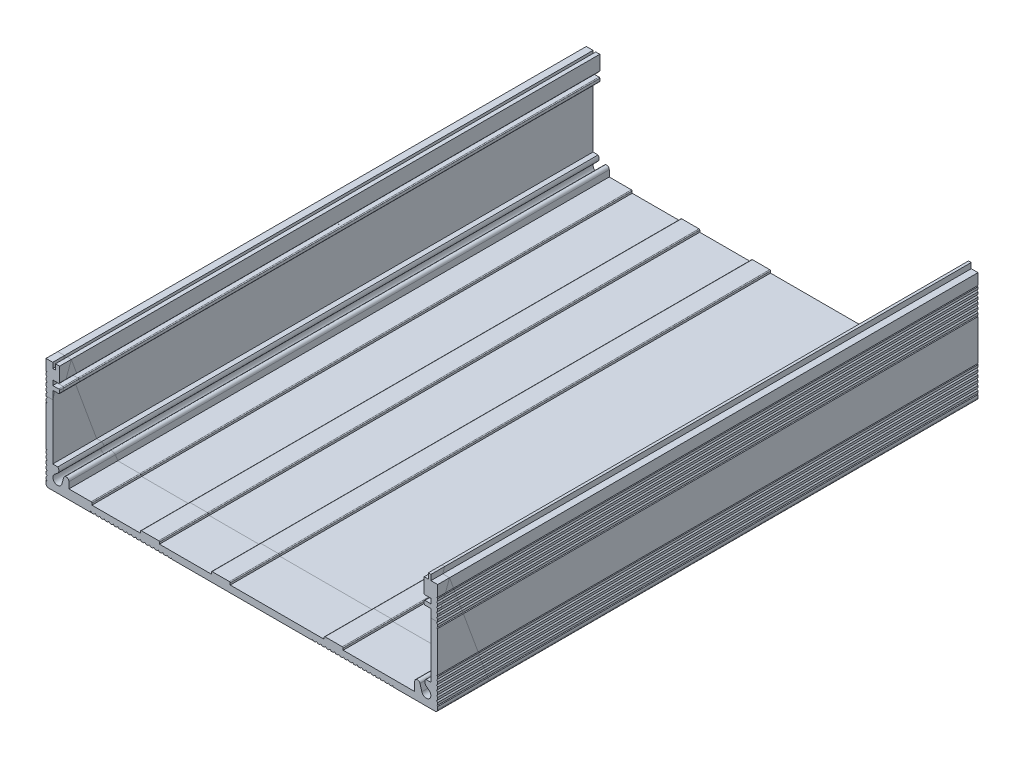
SolidWorks part; units mm, degrees
ref_plane "Front Plane" through (0, 0, 0) normal (0, 0, 1) x (1, 0, 0)
ref_plane "Top Plane" through (0, 0, 0) normal (0, 1, 0) x (1, 0, 0)
ref_plane "Right Plane" through (0, 0, 0) normal (1, 0, 0) x (0, 0, -1)
sketch "Sketch1" plane through (0, 0, 0) normal (0, 0, 1) x (1, 0, 0)
  line L2 (-72.5, -41.1) -> (-72.5, 0)
  line L11 (-70, -32.6) -> (-68.132, -32.6)
  line L12 (-69.2793, -35.507) -> (-68.3418, -34.7938)
  line L14 (-65.9634, -34.9834) -> (-66.6122, -37.3156)
  line L15 (-72.5, -41.1) -> (72.5, -41.1)
  line L17 (-70, -8.95) -> (-67.5, -8.95)
  line L18 (-67.5, -8.95) -> (-67.5, -7.45)
  line L19 (-67.5, -7.45) -> (-70, -7.45)
  line L20 (-70, -5.65) -> (-67.5, -5.65)
  line L21 (-67.5, -5.65) -> (-67.5, 0)
  line L23 (-70, -5.65) -> (-70, -7.45)
  line L24 (-70, -8.95) -> (-70, -32.6)
  line L25 (0, -46.4474) -> (0, 0) construction
  line L26 (70, -8.95) -> (70, -32.6)
  line L27 (70, -5.65) -> (70, -7.45)
  line L29 (67.5, -5.65) -> (67.5, 0)
  line L30 (70, -5.65) -> (67.5, -5.65)
  line L31 (67.5, -7.45) -> (70, -7.45)
  line L32 (67.5, -8.95) -> (67.5, -7.45)
  line L33 (70, -8.95) -> (67.5, -8.95)
  line L34 (65.9634, -34.9834) -> (66.6122, -37.3156)
  line L35 (64, -35.2514) -> (64, -38.56)
  line L36 (69.2793, -35.507) -> (68.3418, -34.7938)
  line L37 (70, -32.6) -> (68.132, -32.6)
  line L39 (72.5, -41.1) -> (72.5, 0)
  line L40 (67.5, 0) -> (69, 0)
  line L41 (69, 0) -> (69, 2)
  line L42 (69, 2) -> (70, 2)
  line L43 (70, 2) -> (70, 0)
  line L44 (70, 0) -> (72.5, 0)
  line L45 (-72.5, 0) -> (-70, 0)
  line L46 (-70, 0) -> (-70, -2)
  line L47 (-70, -2) -> (-69, -2)
  line L48 (-69, -2) -> (-69, 0)
  line L49 (-69, 0) -> (-67.5, 0)
  line L50 (-64, -37.6) -> (-55.5, -37.6)
  line L51 (-55.5, -37.6) -> (-55.5, -38.56)
  line L52 (-55.5, -38.56) -> (-37.5, -38.56)
  line L53 (-37.5, -38.56) -> (-37.5, -37.6)
  line L54 (-37.5, -37.6) -> (-30.5, -37.6)
  line L55 (-30.5, -37.6) -> (-30.5, -38.56)
  line L56 (-4.3, -38.56) -> (30.5, -38.56)
  line L57 (-4.3, -38.56) -> (-4.3, -37.6)
  line L58 (-4.3, -37.6) -> (-11.3, -37.6)
  line L59 (-11.3, -37.6) -> (-11.3, -38.56)
  line L60 (-11.3, -38.56) -> (-30.5, -38.56)
  line L61 (30.5, -38.56) -> (30.5, -37.6)
  line L62 (30.5, -37.6) -> (37.5, -37.6)
  line L63 (37.5, -37.6) -> (37.5, -38.56)
  line L64 (37.5, -38.56) -> (64, -38.56)
  line L65 (-64, -35.2514) -> (-64, -37.6)
  arc A1 (-69.2793, -35.507) -> (-66.6122, -37.3156) centre (-68.25, -36.86) ccw
  arc A3 (-68.132, -32.6) -> (-68.3418, -34.7938) centre (-69.25, -33.6) cw
  arc A4 (-65.9634, -34.9834) -> (-64, -35.2514) centre (-65, -35.2514) cw
  arc A5 (65.9634, -34.9834) -> (64, -35.2514) centre (65, -35.2514) ccw
  arc A6 (68.132, -32.6) -> (68.3418, -34.7938) centre (69.25, -33.6) ccw
  arc A7 (69.2793, -35.507) -> (66.6122, -37.3156) centre (68.25, -36.86) cw
  point P45 (0, -41.1)
  point P47 (0, -37.1)
  dimension "D5" = 8.5
  dimension "D8" = 8.5
  dimension "D9" = 1.5
  dimension "D10" = 4.24
  dimension "D4" = 35.45
  dimension "D13" = 7.5
  dimension "D6" = 1.7
  dimension "D7" = 7.5
  dimension "D32" = 136.5
  dimension "D2" = 41.1
  dimension "D3" = 72.5
  dimension "D11" = 4.25
  dimension "D12" = 3.25
  dimension "D14" = 2.5
  dimension "D15" = 33.65
  dimension "D16" = 32.15
  dimension "D17" = 5.65
  dimension "D18" = 5
  dimension "D19" = 1
  dimension "D20" = 1
  dimension "D21" = 2
  dimension "D22" = 2
  dimension "D23" = 55.5
  dimension "D24" = 30.5
  dimension "D25" = 7
  dimension "D26" = 4.3
  dimension "D27" = 7
  dimension "D28" = 7
  dimension "D29" = 30.5
  dimension "D30" = 2.54
  dimension "D31" = 3.5
extrude "Boss-Extrude1" add sketch "Sketch1" against normal blind 200
sketch "Sketch3" plane through (0, 0, 0) normal (0, 0, 1) x (1, 0, 0)
  line L0 (-72.0833, -29.1) -> (-72.9167, -29.9333)
  line L1 (-72.5, -41.1) -> (72.5, -41.1) construction
  line L2 (-72.5, 0) -> (-72.5, -41.1) construction
  line L3 (-72.0833, -29.1) -> (-75.0833, -29.1)
  line L4 (-72.0833, -30.7667) -> (-72.9167, -31.6)
  line L5 (-72.9167, -29.9333) -> (-72.0833, -30.7667)
  line L6 (-72.9167, -31.6) -> (-72.0833, -32.4333)
  line L7 (-72.0833, -32.4333) -> (-72.9167, -33.2667)
  line L8 (-72.9167, -33.2667) -> (-72.0833, -34.1)
  line L9 (-72.0833, -34.1) -> (-72.9167, -34.9333)
  line L10 (-72.9167, -34.9333) -> (-72.0833, -35.7667)
  line L11 (-72.0833, -35.7667) -> (-72.9167, -36.6)
  line L12 (-72.9167, -36.6) -> (-72.0833, -37.4333)
  line L13 (-72.0833, -37.4333) -> (-72.9167, -38.2667)
  line L14 (-72.9167, -38.2667) -> (-72.0833, -39.1)
  line L15 (-75.0833, -29.1) -> (-75.0833, -39.1)
  line L16 (-75.0833, -39.1) -> (-72.0833, -39.1)
  line L17 (0, -29.205) -> (0, 29.205) construction
  line L18 (75.0833, -29.1) -> (75.0833, -39.1)
  line L19 (72.0833, -29.1) -> (75.0833, -29.1)
  line L20 (72.0833, -29.1) -> (72.9167, -29.9333)
  line L21 (72.9167, -29.9333) -> (72.0833, -30.7667)
  line L22 (72.0833, -30.7667) -> (72.9167, -31.6)
  line L23 (72.9167, -31.6) -> (72.0833, -32.4333)
  line L24 (72.0833, -32.4333) -> (72.9167, -33.2667)
  line L25 (72.9167, -33.2667) -> (72.0833, -34.1)
  line L26 (72.0833, -34.1) -> (72.9167, -34.9333)
  line L27 (72.9167, -34.9333) -> (72.0833, -35.7667)
  line L28 (72.0833, -35.7667) -> (72.9167, -36.6)
  line L29 (72.9167, -36.6) -> (72.0833, -37.4333)
  line L30 (72.0833, -37.4333) -> (72.9167, -38.2667)
  line L31 (72.9167, -38.2667) -> (72.0833, -39.1)
  line L32 (75.0833, -39.1) -> (72.0833, -39.1)
  line L33 (-72.0833, -4.1) -> (-72.9167, -4.9333)
  line L34 (-72.0833, -4.1) -> (-75.0833, -4.1)
  line L35 (-72.0833, -5.7667) -> (-72.9167, -6.6)
  line L36 (-72.9167, -4.9333) -> (-72.0833, -5.7667)
  line L37 (-72.9167, -6.6) -> (-72.0833, -7.4333)
  line L38 (-72.0833, -7.4333) -> (-72.9167, -8.2667)
  line L39 (-72.9167, -8.2667) -> (-72.0833, -9.1)
  line L40 (-72.0833, -9.1) -> (-72.9167, -9.9333)
  line L41 (-72.9167, -9.9333) -> (-72.0833, -10.7667)
  line L42 (-72.0833, -10.7667) -> (-72.9167, -11.6)
  line L43 (-72.9167, -11.6) -> (-72.0833, -12.4333)
  line L44 (-72.0833, -12.4333) -> (-72.9167, -13.2667)
  line L45 (-72.9167, -13.2667) -> (-72.0833, -14.1)
  line L46 (-75.0833, -4.1) -> (-75.0833, -14.1)
  line L47 (-75.0833, -14.1) -> (-72.0833, -14.1)
  line L48 (75.0833, -14.1) -> (72.0833, -14.1)
  line L49 (75.0833, -4.1) -> (75.0833, -14.1)
  line L50 (72.9167, -13.2667) -> (72.0833, -14.1)
  line L51 (72.0833, -12.4333) -> (72.9167, -13.2667)
  line L52 (72.9167, -11.6) -> (72.0833, -12.4333)
  line L53 (72.0833, -10.7667) -> (72.9167, -11.6)
  line L54 (72.9167, -9.9333) -> (72.0833, -10.7667)
  line L55 (72.0833, -9.1) -> (72.9167, -9.9333)
  line L56 (72.9167, -8.2667) -> (72.0833, -9.1)
  line L57 (72.0833, -7.4333) -> (72.9167, -8.2667)
  line L58 (72.9167, -6.6) -> (72.0833, -7.4333)
  line L59 (72.9167, -4.9333) -> (72.0833, -5.7667)
  line L60 (72.0833, -5.7667) -> (72.9167, -6.6)
  line L61 (72.0833, -4.1) -> (75.0833, -4.1)
  line L62 (72.0833, -4.1) -> (72.9167, -4.9333)
  line L67 (-55.1234, -41.497) -> (-55.9567, -40.6637)
  line L68 (-54.2901, -40.6637) -> (-55.1234, -41.497)
  line L69 (-53.4567, -41.497) -> (-54.2901, -40.6637)
  line L70 (-52.6234, -40.6637) -> (-53.4567, -41.497)
  line L71 (-51.7901, -41.497) -> (-52.6234, -40.6637)
  line L72 (-50.9567, -40.6637) -> (-51.7901, -41.497)
  line L73 (-50.1234, -41.497) -> (-50.9567, -40.6637)
  line L74 (-49.2901, -40.6637) -> (-50.1234, -41.497)
  line L75 (-48.4567, -41.497) -> (-49.2901, -40.6637)
  line L76 (-46.7901, -41.497) -> (-47.6234, -40.6637)
  line L77 (-47.6234, -40.6637) -> (-48.4567, -41.497)
  line L79 (-45.9567, -40.6637) -> (-46.7901, -41.497)
  line L95 (-45.1234, -41.497) -> (-45.9567, -40.6637)
  line L96 (-44.2901, -40.6637) -> (-45.1234, -41.497)
  line L97 (-43.4567, -41.497) -> (-44.2901, -40.6637)
  line L98 (-42.6234, -40.6637) -> (-43.4567, -41.497)
  line L99 (-41.7901, -41.497) -> (-42.6234, -40.6637)
  line L100 (-40.9567, -40.6637) -> (-41.7901, -41.497)
  line L101 (-40.1234, -41.497) -> (-40.9567, -40.6637)
  line L102 (-39.2901, -40.6637) -> (-40.1234, -41.497)
  line L103 (-38.4567, -41.497) -> (-39.2901, -40.6637)
  line L104 (-36.7901, -41.497) -> (-37.6234, -40.6637)
  line L105 (-37.6234, -40.6637) -> (-38.4567, -41.497)
  line L106 (-35.9567, -40.6637) -> (-36.7901, -41.497)
  line L107 (-55.9567, -40.6637) -> (-55.9567, -45.4119)
  line L108 (-35.1234, -41.497) -> (-35.9567, -40.6637)
  line L109 (-34.2901, -40.6637) -> (-35.1234, -41.497)
  line L110 (-33.4567, -41.497) -> (-34.2901, -40.6637)
  line L111 (-32.6234, -40.6637) -> (-33.4567, -41.497)
  line L112 (-31.7901, -41.497) -> (-32.6234, -40.6637)
  line L113 (-30.9567, -40.6637) -> (-31.7901, -41.497)
  line L114 (-30.1234, -41.497) -> (-30.9567, -40.6637)
  line L115 (-29.2901, -40.6637) -> (-30.1234, -41.497)
  line L116 (-28.4567, -41.497) -> (-29.2901, -40.6637)
  line L117 (-26.7901, -41.497) -> (-27.6234, -40.6637)
  line L118 (-27.6234, -40.6637) -> (-28.4567, -41.497)
  line L119 (-25.9567, -40.6637) -> (-26.7901, -41.497)
  line L120 (-25.9567, -40.6637) -> (-25.9567, -45.4119)
  line L121 (-25.9567, -45.4119) -> (-55.9567, -45.4119)
  line L122 (25.9567, -45.4119) -> (55.9567, -45.4119)
  line L123 (25.9567, -40.6637) -> (25.9567, -45.4119)
  line L124 (25.9567, -40.6637) -> (26.7901, -41.497)
  line L125 (27.6234, -40.6637) -> (28.4567, -41.497)
  line L126 (26.7901, -41.497) -> (27.6234, -40.6637)
  line L127 (28.4567, -41.497) -> (29.2901, -40.6637)
  line L128 (29.2901, -40.6637) -> (30.1234, -41.497)
  line L129 (30.1234, -41.497) -> (30.9567, -40.6637)
  line L130 (30.9567, -40.6637) -> (31.7901, -41.497)
  line L131 (31.7901, -41.497) -> (32.6234, -40.6637)
  line L132 (32.6234, -40.6637) -> (33.4567, -41.497)
  line L133 (33.4567, -41.497) -> (34.2901, -40.6637)
  line L134 (34.2901, -40.6637) -> (35.1234, -41.497)
  line L135 (35.1234, -41.497) -> (35.9567, -40.6637)
  line L136 (55.9567, -40.6637) -> (55.9567, -45.4119)
  line L137 (35.9567, -40.6637) -> (36.7901, -41.497)
  line L138 (37.6234, -40.6637) -> (38.4567, -41.497)
  line L139 (36.7901, -41.497) -> (37.6234, -40.6637)
  line L140 (38.4567, -41.497) -> (39.2901, -40.6637)
  line L141 (39.2901, -40.6637) -> (40.1234, -41.497)
  line L142 (40.1234, -41.497) -> (40.9567, -40.6637)
  line L143 (40.9567, -40.6637) -> (41.7901, -41.497)
  line L144 (41.7901, -41.497) -> (42.6234, -40.6637)
  line L145 (42.6234, -40.6637) -> (43.4567, -41.497)
  line L146 (43.4567, -41.497) -> (44.2901, -40.6637)
  line L147 (44.2901, -40.6637) -> (45.1234, -41.497)
  line L148 (45.1234, -41.497) -> (45.9567, -40.6637)
  line L149 (45.9567, -40.6637) -> (46.7901, -41.497)
  line L150 (47.6234, -40.6637) -> (48.4567, -41.497)
  line L151 (46.7901, -41.497) -> (47.6234, -40.6637)
  line L152 (48.4567, -41.497) -> (49.2901, -40.6637)
  line L153 (49.2901, -40.6637) -> (50.1234, -41.497)
  line L154 (50.1234, -41.497) -> (50.9567, -40.6637)
  line L155 (50.9567, -40.6637) -> (51.7901, -41.497)
  line L156 (51.7901, -41.497) -> (52.6234, -40.6637)
  line L157 (52.6234, -40.6637) -> (53.4567, -41.497)
  line L158 (53.4567, -41.497) -> (54.2901, -40.6637)
  line L159 (54.2901, -40.6637) -> (55.1234, -41.497)
  line L160 (55.1234, -41.497) -> (55.9567, -40.6637)
  point P3 (-72.5, -29.5167)
  point P12 (-72.5, -31.1833)
  point P17 (-72.5, -32.85)
  point P21 (-72.5, -37.85)
  point P22 (-72.5, -34.5167)
  point P23 (-72.7303, -15.2632)
  point P27 (-72.5, -36.1833)
  point P28 (-72.7303, -16.9299)
  point P49 (-72.5, -4.5167)
  point P51 (-72.7303, -13.5965)
  point P52 (-72.7303, -18.5965)
  point P57 (-72.5, -6.1833)
  point P61 (-72.5, -7.85)
  point P64 (-72.5, -12.85)
  point P65 (-72.5, -9.5167)
  point P67 (-72.5, -11.1833)
  point P82 (72.5, -11.1833)
  point P83 (72.5, -9.5167)
  point P84 (72.5, -12.85)
  point P85 (72.5, -7.85)
  point P86 (72.5, -6.1833)
  point P87 (72.5, -4.5167)
  point P105 (-53.0401, -41.0804)
  point P106 (-51.3734, -41.0804)
  point P107 (-54.7067, -41.0804)
  point P108 (-49.7067, -41.0804)
  point P109 (-48.0401, -41.0804)
  point P110 (-46.3734, -41.0804)
  point P147 (-43.0401, -41.0804)
  point P148 (-41.3734, -41.0804)
  point P149 (-44.7067, -41.0804)
  point P150 (-39.7067, -41.0804)
  point P151 (-38.0401, -41.0804)
  point P152 (-36.3734, -41.0804)
  point P168 (-33.0401, -41.0804)
  point P169 (-31.3734, -41.0804)
  point P170 (-34.7067, -41.0804)
  point P171 (-29.7067, -41.0804)
  point P172 (-28.0401, -41.0804)
  point P173 (-26.3734, -41.0804)
  point P185 (26.3734, -41.0804)
  point P186 (28.0401, -41.0804)
  point P187 (29.7067, -41.0804)
  point P188 (34.7067, -41.0804)
  point P189 (31.3734, -41.0804)
  point P190 (33.0401, -41.0804)
  point P191 (36.3734, -41.0804)
  point P192 (38.0401, -41.0804)
  point P193 (39.7067, -41.0804)
  point P194 (44.7067, -41.0804)
  point P195 (41.3734, -41.0804)
  point P196 (43.0401, -41.0804)
  point P197 (46.3734, -41.0804)
  point P198 (48.0401, -41.0804)
  point P199 (49.7067, -41.0804)
  point P200 (54.7067, -41.0804)
  point P201 (51.3734, -41.0804)
  point P202 (53.0401, -41.0804)
  dimension "D1" = 10
  dimension "D2" = 2
  dimension "D3" = 6
  dimension "D5" = 3
extrude "Cut-Extrude1" cut sketch "Sketch3" against normal through all
fillet "Fillet1" radius 1 2 edges at (72.5, -41.1, -100) (-72.5, -41.1, -100)
fillet "Fillet3" radius 0.3 13 edges at (67.5, -8.95, -100) (67.5, -7.45, -100) (37.5, -37.6, -100) (30.5, -37.6, -100) (-4.3, -37.6, -100) (-11.3, -37.6, -100) (-30.5, -37.6, -100) (-37.5, -37.6, -100) (-55.5, -37.6, -100) (-67.5, -8.95, -100) (-67.5, -7.45, -100) (67.5, -5.65, -100) (-67.5, -5.65, -100)
sketch "Sketch2" plane through (0, 0, 0) normal (0, 0, 1) x (1, 0, 0)
  line L0 (-86.5381, -12) -> (90.1251, -12) construction
  line L1 (-86.5381, 12) -> (90.1251, 12) construction
  point P8 (1.7935, 12)
  dimension "D1" = 12
  dimension "D2" = 12
ref_plane "Plane3" through (0, -1.4037, -3.8567) normal (0, 0.342, 0.9397) x (1, 0, 0)
split "Split1" trim tools "Plane3" bodies to split 119 resulting bodies 114 115 116
ref_plane "Plane4" through (0, 1.4037, -3.8567) normal (0, -0.342, 0.9397) x (1, 0, 0)
split "Split2" trim tools "Plane4" bodies to split 114 resulting bodies 117 118
